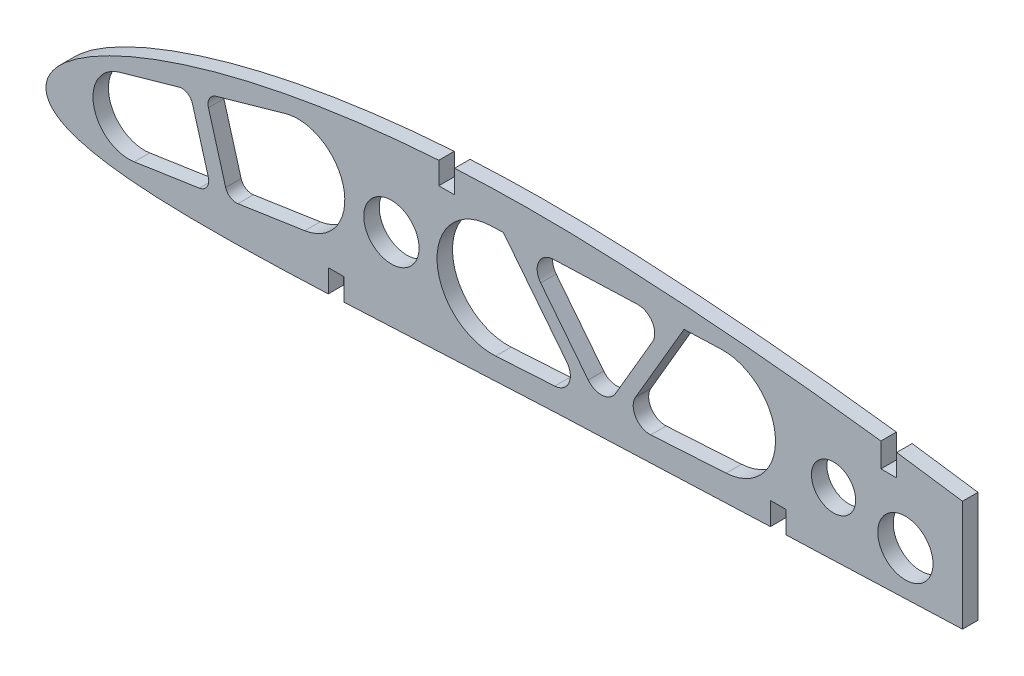
SolidWorks part; units mm, degrees
material "Фанера"
ref_plane "Front Plane" through (0, 0, 0) normal (0, 0, 1) x (1, 0, 0)
ref_plane "Top Plane" through (0, 0, 0) normal (0, 1, 0) x (1, 0, 0)
ref_plane "Right Plane" through (0, 0, 0) normal (1, 0, 0) x (0, 0, -1)
curve "Кривая5"
  spline degree 3 poles (0.048, 0.6214, 0) (0.0227, 0.3735, 0) (-0.0278, -0.1225, 0) (0.078, -0.8844, 0) (0.3497, -1.6388, 0) (0.8143, -2.3651, 0) (1.4635, -3.0393, 0) (2.291, -3.661, 0) (3.3059, -4.2358, 0) (4.5353, -4.7737, 0) (6.0297, -5.2822, 0) (7.869, -5.7653, 0) (10.1688, -6.2217, 0) (13.0754, -6.6396, 0) (16.7281, -6.993, 0) (21.19, -7.2473, 0) (26.4, -7.3766, 0) (32.1974, -7.3763, 0) (38.3978, -7.2614, 0) (44.8576, -7.0566, 0) (51.4865, -6.7865, 0) (58.231, -6.4723, 0) (65.0521, -6.1329, 0) (71.9108, -5.784, 0) (78.7714, -5.4397, 0) (85.6105, -5.111, 0) (92.4321, -4.805, 0) (99.255, -4.532, 0) (106.0974, -4.2783, 0) (112.9692, -4.0031, 0) (119.8644, -3.7232, 0) (126.7739, -3.4401, 0) (133.6816, -3.1587, 0) (140.5819, -2.8824, 0) (147.472, -2.6139, 0) (154.3526, -2.3556, 0) (161.225, -2.1094, 0) (168.0909, -1.8766, 0) (174.9516, -1.6586, 0) (181.8086, -1.4564, 0) (188.6632, -1.2704, 0) (195.5166, -1.1011, 0) (202.3695, -0.9486, 0) (209.2212, -0.8129, 0) (216.0668, -0.6936, 0) (222.8864, -0.5903, 0) (229.6176, -0.5029, 0) (236.0874, -0.4315, 0) (241.9808, -0.3765, 0) (246.559, -0.3395, 0) (249.1205, -0.3213, 0) (250, -0.315, 0) knots 0 0 0 0 0.002941 0.005884 0.009016 0.012365 0.016008 0.020037 0.024574 0.029784 0.035897 0.04324 0.052276 0.063635 0.077983 0.095698 0.11652 0.139661 0.164312 0.189919 0.216157 0.242838 0.269834 0.296993 0.324123 0.351139 0.378036 0.404946 0.431961 0.459078 0.486347 0.513641 0.540929 0.568176 0.59538 0.622543 0.649673 0.676775 0.703855 0.730919 0.757971 0.785018 0.812062 0.839103 0.866132 0.893099 0.919831 0.94581 0.969681 0.98959 1 1 1 1
curve "Кривая6"
  spline degree 3 poles (250, 0.315, 0) (249.1557, 0.545, 0) (246.7202, 1.2085, 0) (242.3913, 2.3583, 0) (236.8498, 3.7876, 0) (230.7799, 5.298, 0) (224.4559, 6.8129, 0) (218.0305, 8.2916, 0) (211.5624, 9.7197, 0) (205.0724, 11.0924, 0) (198.568, 12.4079, 0) (192.0524, 13.6653, 0) (185.5276, 14.8641, 0) (178.9953, 16.0034, 0) (172.4571, 17.0824, 0) (165.9143, 18.0998, 0) (159.3687, 19.0545, 0) (152.8218, 19.9449, 0) (146.2754, 20.7693, 0) (139.7314, 21.5257, 0) (133.1918, 22.212, 0) (126.6587, 22.8257, 0) (120.1368, 23.364, 0) (113.6286, 23.8247, 0) (107.1527, 24.2002, 0) (100.7411, 24.4984, 0) (94.4118, 24.6866, 0) (88.1559, 24.7401, 0) (81.949, 24.6588, 0) (75.7805, 24.441, 0) (69.6537, 24.0819, 0) (63.5754, 23.578, 0) (57.5552, 22.9249, 0) (51.6058, 22.1191, 0) (45.7444, 21.1566, 0) (39.9959, 20.0354, 0) (34.3979, 18.7563, 0) (29.0104, 17.3276, 0) (23.9258, 15.7719, 0) (19.2707, 14.1343, 0) (15.1791, 12.4833, 0) (11.7405, 10.8956, 0) (8.9594, 9.4296, 0) (6.7609, 8.1086, 0) (5.0337, 6.9246, 0) (3.6717, 5.8542, 0) (2.5921, 4.8713, 0) (1.7382, 3.9526, 0) (1.0699, 3.0809, 0) (0.5716, 2.2416, 0) (0.2158, 1.4308, 0) (0.1023, 0.8832, 0) (0.048, 0.6214, 0) knots 0 0 0 0 0.010162 0.029313 0.052012 0.076619 0.101948 0.127526 0.153184 0.178868 0.204558 0.230246 0.255926 0.281594 0.307246 0.332878 0.358485 0.384061 0.409603 0.435104 0.460559 0.485959 0.511303 0.536552 0.561723 0.586629 0.611085 0.635251 0.659272 0.683164 0.706922 0.730536 0.753983 0.777235 0.800246 0.822951 0.845237 0.866916 0.887662 0.906968 0.924203 0.938879 0.950932 0.960693 0.968647 0.975233 0.980795 0.985584 0.989782 0.993521 0.996902 1 1 1 1
sketch "Эскиз1" plane through (0, 0, 0) normal (0, 0, 1) x (1, 0, 0)
  line L1 (62.5, -18.1817) -> (62.5, 45.0278) construction
  line L2 (51.075, -6.7979) -> (51.075, -2.671)
  line L3 (51.075, -2.671) -> (53.925, -2.671)
  line L4 (53.925, -2.671) -> (53.925, -6.671)
  line L5 (71.075, 24.1537) -> (71.075, 20.1537)
  line L6 (71.075, 20.1537) -> (73.925, 20.1537)
  line L7 (73.925, 20.1537) -> (73.925, 24.3235)
  line L8 (131.075, -3.2651) -> (131.075, 0.8503)
  line L9 (131.075, 0.8503) -> (133.925, 0.8503)
  line L10 (133.925, 0.8503) -> (133.925, -3.1497)
  line L11 (151.075, 20.1603) -> (151.075, 15.7885)
  line L12 (151.075, 15.7885) -> (153.925, 15.7885)
  line L13 (153.925, 15.7885) -> (153.925, 19.7885)
  line L15 (15, -6.8191) -> (15, 12.369) construction
  line L16 (43.2406, 17.5692) -> (30.7698, 14.0205)
  line L17 (34.7307, -0.8313) -> (46.8309, 0.9882)
  line L18 (91.7605, 18.9955) -> (107.0422, 19.5445)
  line L19 (81.3551, -1.3883) -> (92.0623, -0.7469)
  line L20 (82.757, 18.6721) -> (94.239, 4.1049)
  line L21 (89.5122, 14.1404) -> (98.1062, 3.2371)
  line L22 (103.0529, 3.5814) -> (109.7405, 15.0337)
  line L23 (106.6602, 4.8011) -> (115.446, 19.8465)
  line L24 (82.757, 18.6721) -> (80.398, 18.5873)
  line L26 (123.0681, 1.1108) -> (109.4303, 0.2937)
  line L27 (26.5081, 10.7284) -> (29.3777, 0.6444)
  line L28 (32.5096, 0.5991) -> (29.3936, 11.5495)
  line L29 (24.0371, 12.1046) -> (13.221, 9.0267)
  line L30 (27.7514, -1.8807) -> (15.9665, -3.6528)
  line L31 (115.446, 19.8465) -> (122.1589, 20.0876)
  line L32 (165.8402, 18.1005) -> (165.8402, -1.9537)
  circle A0 centre (62.5, 8.5938) radius 5
  circle A1 centre (142.5, 8.5938) radius 4
  arc A4 (13.221, 9.0267) -> (15.9665, -3.6528) centre (15, 2.7749) ccw
  arc A5 (46.8309, 0.9882) -> (43.2406, 17.5692) centre (45.567, 9.3938) ccw
  arc A6 (80.398, 18.5873) -> (81.3551, -1.3883) centre (80.757, 8.5938) ccw
  arc A7 (123.0681, 1.1108) -> (122.1589, 20.0876) centre (122.5, 10.5938) ccw
  arc A8 (98.1062, 3.2371) -> (103.0529, 3.5814) centre (100.4623, 5.0942) ccw
  arc A9 (92.0623, -0.7469) -> (94.239, 4.1049) centre (91.8829, 2.2478) ccw
  arc A10 (89.5122, 14.1404) -> (91.7605, 18.9955) centre (91.8682, 15.9975) cw
  arc A11 (109.7405, 15.0337) -> (107.0422, 19.5445) centre (107.1499, 16.5465) ccw
  arc A12 (109.4303, 0.2937) -> (106.6602, 4.8011) centre (109.2509, 3.2883) cw
  arc A13 (29.3936, 11.5495) -> (30.7698, 14.0205) centre (31.3172, 12.0968) cw
  arc A14 (26.5081, 10.7284) -> (24.0371, 12.1046) centre (24.5845, 10.181) ccw
  arc A15 (32.5096, 0.5991) -> (34.7307, -0.8313) centre (34.4333, 1.1465) ccw
  arc A16 (27.7514, -1.8807) -> (29.3777, 0.6444) centre (27.454, 0.097) ccw
  circle A19 centre (155.5, 5.5938) radius 5
  spline S2 degree 3 poles (0.048, 0.6214) (0.0227, 0.3735) (-0.0278, -0.1225) (0.078, -0.8844) (0.3497, -1.6388) (0.8143, -2.3651) (1.4635, -3.0393) (2.291, -3.661) (3.3059, -4.2358) (4.5353, -4.7737) (6.0297, -5.2822) (7.869, -5.7653) (10.1688, -6.2217) (13.0754, -6.6396) (16.7281, -6.993) (21.19, -7.2473) (26.4, -7.3766) (32.1974, -7.3763) (38.3978, -7.2614) (44.7329, -7.0606) (48.9849, -6.8884) (51.075, -6.7979) knots 0 0 0 0 0.002941 0.005884 0.009016 0.012365 0.016008 0.020037 0.024574 0.029784 0.035897 0.04324 0.052276 0.063635 0.077983 0.095698 0.11652 0.139661 0.164312 0.189919 0.214681 0.214681 0.214681 0.214681
  spline S3 degree 3 poles (165.8402, 18.1005) (163.6832, 18.4252) (159.7137, 19.004) (155.7392, 19.5478) (153.925, 19.7885) knots 0.333154 0.333154 0.333154 0.333154 0.358485 0.379737 0.379737 0.379737 0.379737
  spline S4 degree 3 poles (151.075, 20.1603) (149.4743, 20.3656) (145.6936, 20.8365) (139.7314, 21.5257) (133.1918, 22.212) (126.6587, 22.8257) (120.1368, 23.364) (113.6286, 23.8247) (107.1527, 24.2002) (100.7411, 24.4984) (94.4118, 24.6866) (88.1559, 24.7401) (81.949, 24.6588) (77.2098, 24.4915) (74.5399, 24.3567) (73.925, 24.3235) knots 0.390862 0.390862 0.390862 0.390862 0.409603 0.435104 0.460559 0.485959 0.511303 0.536552 0.561723 0.586629 0.611085 0.635251 0.659272 0.683164 0.690315 0.690315 0.690315 0.690315
  spline S5 degree 3 poles (133.925, -3.1497) (136.1452, -3.06) (140.6619, -2.8793) (147.472, -2.6139) (154.3526, -2.3556) (160.4743, -2.1363) (164.3026, -2.0053) (165.8402, -1.9537) knots 0.541876 0.541876 0.541876 0.541876 0.568176 0.59538 0.622543 0.649673 0.667883 0.667883 0.667883 0.667883
  spline S6 degree 3 poles (53.925, -6.671) (55.3515, -6.606) (59.0561, -6.4313) (65.0521, -6.1329) (71.9108, -5.784) (78.7714, -5.4397) (85.6105, -5.111) (92.4321, -4.805) (99.255, -4.532) (106.0974, -4.2783) (112.9692, -4.0031) (119.8644, -3.7232) (125.9039, -3.4757) (129.6414, -3.3233) (131.075, -3.2651) knots 0.225936 0.225936 0.225936 0.225936 0.242838 0.269834 0.296993 0.324123 0.351139 0.378036 0.404946 0.431961 0.459078 0.486347 0.513641 0.530623 0.530623 0.530623 0.530623
  spline S7 degree 3 poles (71.075, 24.1537) (70.5976, 24.1226) (68.0914, 23.9524) (63.5754, 23.578) (57.5552, 22.9249) (51.6058, 22.1191) (45.7444, 21.1566) (39.9959, 20.0354) (34.3979, 18.7563) (29.0104, 17.3276) (23.9258, 15.7719) (19.2707, 14.1343) (15.1791, 12.4833) (11.7405, 10.8956) (8.9594, 9.4296) (6.7609, 8.1086) (5.0337, 6.9246) (3.6717, 5.8542) (2.5921, 4.8713) (1.7382, 3.9526) (1.0699, 3.0809) (0.5716, 2.2416) (0.2158, 1.4308) (0.1023, 0.8832) (0.048, 0.6214) knots 0.701366 0.701366 0.701366 0.701366 0.706922 0.730536 0.753983 0.777235 0.800246 0.822951 0.845237 0.866916 0.887662 0.906968 0.924203 0.938879 0.950932 0.960693 0.968647 0.975233 0.980795 0.985584 0.989782 0.993521 0.996902 1 1 1 1
  point P10 (62.5, -6.2594)
  point P11 (62.5, 23.4469)
  point P26 (152.5, 15.7885)
  point P29 (132.5, 0.8503)
  point P30 (72.5, 20.1537)
  point P31 (52.5, -2.671)
  point P65 (100.8322, -0.2214)
  point P74 (103.8322, -0.0417)
  point P82 (25.9608, 12.652)
  point P87 (30, -1.5426)
  dimension "D1" = 10
  dimension "D2" = 8
  dimension "D34" = 13
  dimension "D36" = 17
  dimension "D39" = 20
  dimension "D40" = 19
  dimension "D49" = 3
  dimension "D46" = 3
  dimension "D44" = 3
  dimension "D48" = 3
  dimension "D50" = 3
  dimension "D53" = 2
  dimension "D54" = 2
  dimension "D55" = 2
  dimension "D56" = 2
  dimension "D60" = 10
  dimension "D3" = 62.5
  dimension "D4" = 80
  dimension "D7" = 2.85
  dimension "D8" = 2.85
  dimension "D9" = 2.85
  dimension "D10" = 2.85
  dimension "D11" = 10
  dimension "D12" = 10
  dimension "D13" = 10
  dimension "D14" = 10
  dimension "D15" = 4
  dimension "D16" = 4
  dimension "D17" = 4
  dimension "D18" = 4
  dimension "D22" = 0.6214
  dimension "D23" = 2.671
  dimension "D24" = 19.5323
  dimension "D25" = 15.1671
  dimension "D26" = 0.2289
  dimension "D27" = 7.4193
  dimension "D28" = 3.8865
  dimension "D29" = 23.702
  dimension "D30" = 19.5389
  dimension "D5" = 29.7062
  dimension "D31" = 14.8531
  dimension "D35" = 15
  dimension "D37" = 16.933
  dimension "D38" = 0.8
  dimension "D41" = 18.257
  dimension "D42" = 20
  dimension "D43" = 2
  dimension "D45" = 2
  dimension "D47" = 3
  dimension "D51" = 3
  dimension "D52" = 15
  dimension "D57" = 19.7053
  dimension "D58" = 2.5
  dimension "D59" = 2.5
  dimension "D61" = 13
  dimension "D62" = 3
  dimension "D63" = 23.3402
  dimension "D64" = 10.5475
  dimension "D65" = 9.5067
  dimension "D19" = 0.048
extrude "Бобышка-Вытянуть1" add sketch "Эскиз1" along normal blind 2.8
equation "\"t\"= 2.85"
equation "\"D7@Эскиз1\"=\"t\""
equation "\"D8@Эскиз1\"=\"t\""
equation "\"D9@Эскиз1\"=\"t\""
equation "\"D10@Эскиз1\"=\"t\""
equation "\"D31@Эскиз1\"=\"D5@Эскиз1\"/2"
